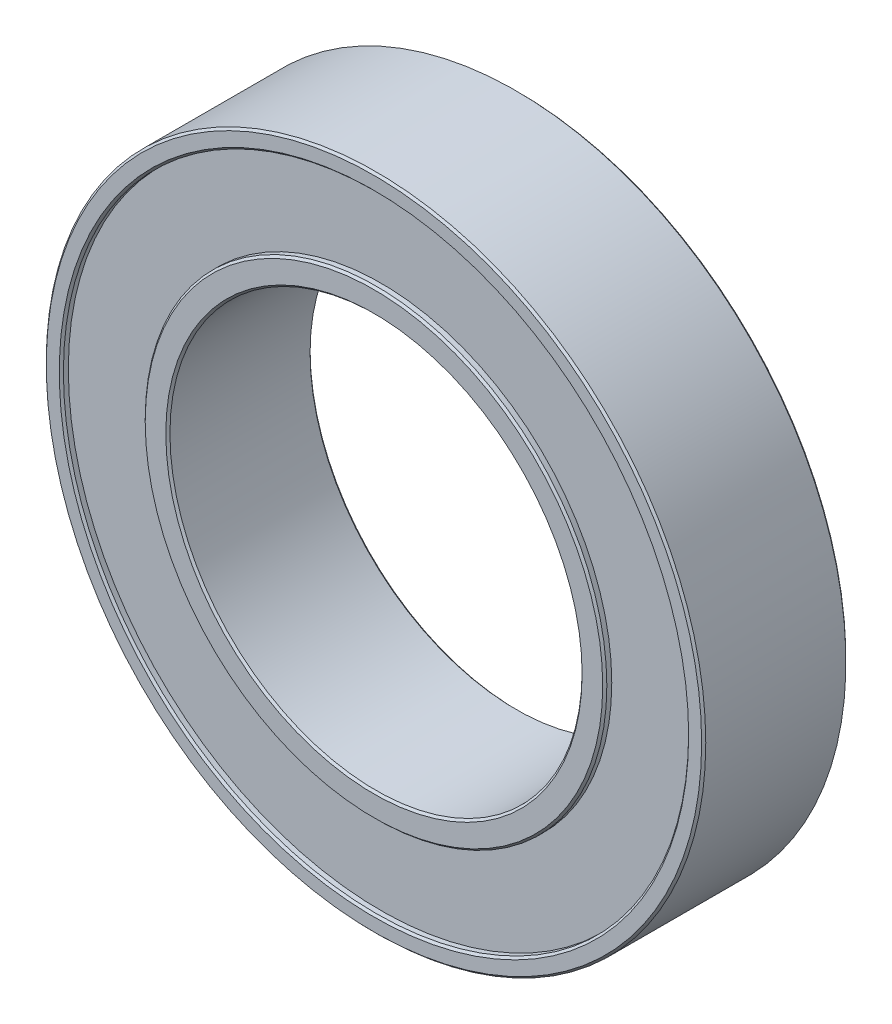
SolidWorks part; units mm, degrees
ref_plane "Front Plane" through (0, 0, 0) normal (0, 0, 1) x (1, 0, 0)
ref_plane "Top Plane" through (0, 0, 0) normal (0, 1, 0) x (1, 0, 0)
ref_plane "Right Plane" through (0, 0, 0) normal (1, 0, 0) x (0, 0, -1)
ref_axis "Axis1" through (0, 0, -19.0783) along (0, 0, 1)
sketch "Sketch1" plane through (0, 0, 0) normal (1, 0, 0) x (0, 0, -1)
  line L0 (19.0783, 0) -> (-24.5011, 0) construction
  line L1 (-3.5, 16) -> (3.5, 16)
  line L2 (-3.5, 16) -> (-3.5, 10) construction
  line L3 (-3.5, 10) -> (3.5, 10)
  line L4 (3.5, 16) -> (3.5, 15.1694)
  line L5 (-3.5, 16) -> (3.5, 10) construction
  line L6 (-3.5, 10) -> (3.5, 16) construction
  line L7 (0, 13) -> (0, 0) construction
  line L8 (3.5, 11.1996) -> (3.5, 10)
  line L9 (3.5, 15.1694) -> (3.1603, 15.1694)
  line L10 (-3.5, 11.1996) -> (-3.5, 10)
  line L11 (3.5, 11.1996) -> (3.1603, 11.1996)
  line L12 (3.1603, 15.1694) -> (3.1603, 11.1996)
  line L13 (-3.5, 11.1996) -> (-3.1603, 11.1996)
  line L14 (-3.1603, 15.1694) -> (-3.1603, 11.1996)
  line L15 (-3.5, 15.1694) -> (-3.1603, 15.1694)
  line L16 (-3.5, 16) -> (-3.5, 15.1694)
  point P0 (0, 13)
  dimension "D1" = 16
  dimension "D2" = 7
  dimension "D3" = 10
revolve "Revolve1" add sketch "Sketch1" angle 360 about axis through (0, 0, -19.0783) along (0, 0, 1)
chamfer "Chamfer1" distance 0.1 angle 45 8 edges at (-10, 0, -3.5) (-10, 0, 3.5) (-16, 0, 3.5) (-16, 0, -3.5) (-15.1694, 0, -3.5) (-11.1996, 0, -3.5) (-15.1694, 0, 3.5) (-11.1996, 0, 3.5)
